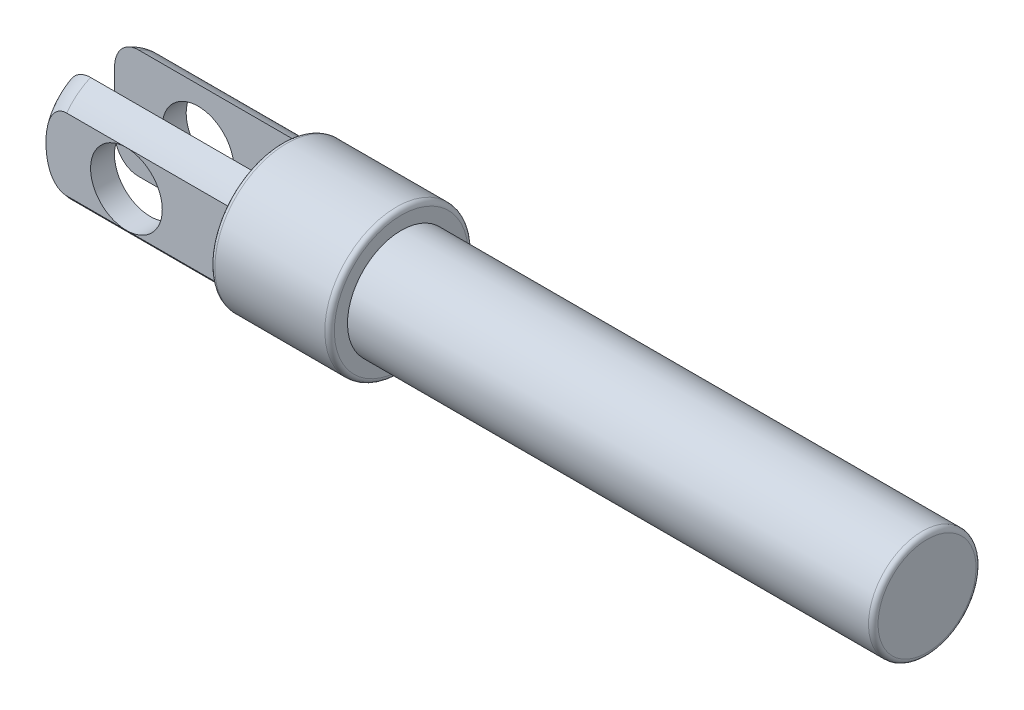
SolidWorks part; units mm, degrees
ref_plane "前视基准面" through (0, 0, 0) normal (0, 0, 1) x (1, 0, 0)
ref_plane "上视基准面" through (0, 0, 0) normal (0, 1, 0) x (1, 0, 0)
ref_plane "右视基准面" through (0, 0, 0) normal (1, 0, 0) x (0, 0, -1)
sketch "草图1" plane through (0, 0, 0) normal (0, 0, 1) x (1, 0, 0)
  line L0 (0, 0) -> (-9, 0) construction
  line L1 (0, 0) -> (0, 2.25)
  line L2 (0, 2.25) -> (-22, 2.25)
  line L3 (-22, 2.25) -> (-22, 3)
  line L4 (-22, 3) -> (-27, 3)
  line L5 (-27, 3) -> (-27, 2.5)
  line L6 (-27, 2.5) -> (-35, 2.5)
  line L7 (-35, 2.5) -> (-35, 0)
  line L8 (-35, 0) -> (0, 0)
  dimension "D1" = 4.5
  dimension "D2" = 6
  dimension "D3" = 5
  dimension "D4" = 22
  dimension "D5" = 5
  dimension "D6" = 35
revolve "旋转1" add sketch "草图1" angle 360 about L0
fillet "圆角1" radius 1 1 edges at (-35, 2.5, 0)
sketch "草图2" plane through (-35, 0, 0) normal (-1, 0, 0) x (0, 0, 1)
  line L5 (-1, 5.1726) -> (-2, 5.1726)
  line L6 (-1, 5.1726) -> (-1, -3.7665)
  line L7 (-1, -3.7665) -> (-2, -3.7665)
  line L8 (-2, 5.1726) -> (-2, -3.7665)
  line L9 (1, 4.5539) -> (2, 4.5539)
  line L10 (1, 4.5539) -> (1, -4.294)
  line L11 (1, -4.294) -> (2, -4.294)
  line L12 (2, 4.5539) -> (2, -4.294)
  circle A0 centre (0, 0) radius 7.3214
  dimension "D1" = 2
  dimension "D2" = 1
  dimension "D3" = 1
  dimension "D4" = 1
extrude "切除-拉伸1" cut sketch "草图2" against normal blind 8
sketch "草图3" plane through (0, 0, -1) normal (0, 0, -1) x (-1, 0, 0)
  circle A0 centre (31.5, 0) radius 1.5
fillet "圆角2" radius 0.2 3 edges at (-22, 3, 0) (-27, 3, 0) (0, 2.25, 0)
extrude "切除-拉伸2" cut sketch "草图3" against normal through all and the other way through all
